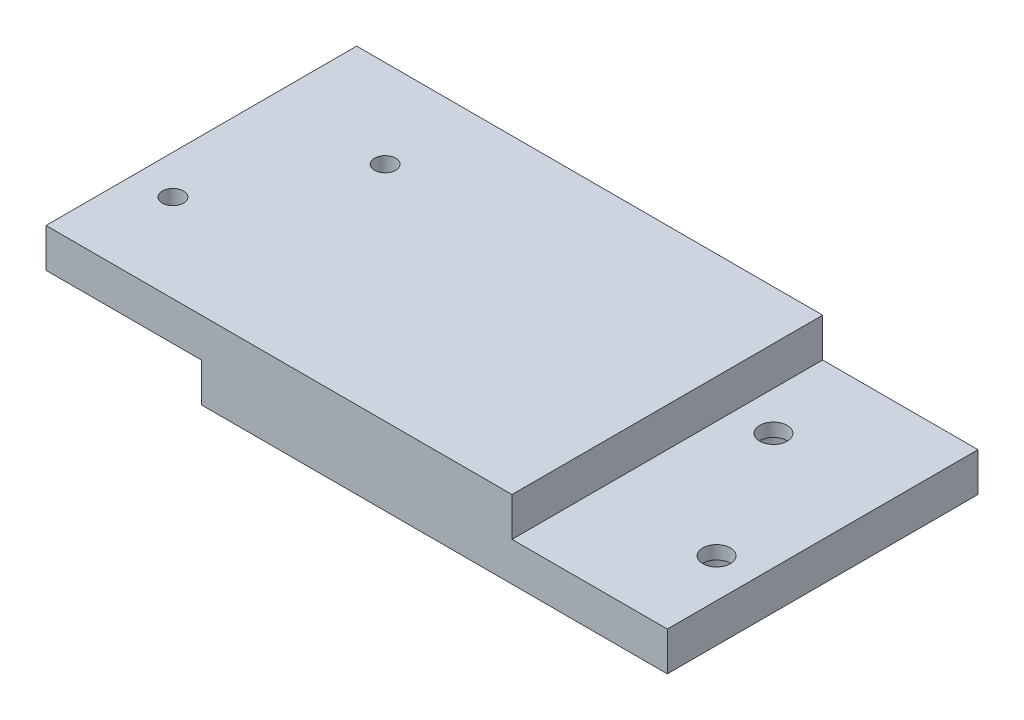
SolidWorks part; units mm, degrees
material "6061-T6 (SS)"
ref_plane "Front Plane" through (0, 0, 0) normal (0, 0, 1) x (1, 0, 0)
ref_plane "Top Plane" through (0, 0, 0) normal (0, 1, 0) x (1, 0, 0)
ref_plane "Right Plane" through (0, 0, 0) normal (1, 0, 0) x (0, 0, -1)
sketch "Sketch1" plane through (0, 0, 0) normal (0, 0, 1) x (1, 0, 0)
  line L1 (0, 0) -> (101.6, 0)
  line L2 (0, 0) -> (0, 12.7)
  line L3 (0, 12.7) -> (101.6, 12.7)
  line L4 (101.6, 0) -> (101.6, 12.7)
  line L5 (0, 0) -> (25.4, 0)
  line L6 (0, 0) -> (0, 6.35)
  line L7 (0, 6.35) -> (25.4, 6.35)
  line L8 (25.4, 0) -> (25.4, 6.35)
  line L9 (101.6, 12.7) -> (76.2, 12.7)
  line L10 (101.6, 12.7) -> (101.6, 6.35)
  line L11 (101.6, 6.35) -> (76.2, 6.35)
  line L12 (76.2, 12.7) -> (76.2, 6.35)
  dimension "D1" = 6.35
  dimension "D2" = 6.35
  dimension "D3" = 12.7
  dimension "D4" = 101.6
  dimension "D5" = 25.4
  dimension "D6" = 25.4
extrude "Boss-Extrude1" add sketch "Sketch1" along normal blind 50.8 contours L12 L3 L2 L7 L8 L1 L4 L11
sketch "Sketch2" plane through (0, 0, 0) normal (0, 1, 0) x (1, 0, 0)
  line L0 (6.35, -36.3985) -> (19.05, -14.4015) construction
  line L1 (19.05, -14.4015) -> (82.55, -14.4015) construction
  line L2 (82.55, -14.4015) -> (95.25, -36.3985) construction
  line L3 (95.25, -36.3985) -> (6.35, -36.3985) construction
  line L4 (101.6, -50.8) -> (101.6, 0) construction
  line L5 (6.35, -36.3985) -> (0, -36.3985) construction
  line L6 (0, -50.8) -> (0, 0) construction
  line L7 (95.25, -36.3985) -> (101.6, -36.3985) construction
  point P7 (101.6, -25.4)
  point P8 (88.9, -25.4)
  dimension "D1" = 120
  dimension "D2" = 120
  dimension "D3" = 63.5
  dimension "D4" = 88.9
hole_wizard "#8-32 Tapped Hole1" positions "Sketch3" profile "Sketch5" tap size "#8-32" standard "ANSI Inch" end condition through all
sketch "Sketch3" plane through (0, 12.7, 0) normal (0, 1, 0) x (1, 0, 0)
  point P0 (6.35, -36.3985)
  point P3 (19.05, -14.4015)
sketch "Sketch5" plane through (6.35, 12.7, 36.3985) normal (1, 0, 0) x (0, 0, 1)
  line L0 (0, 0) -> (0, 12.7)
  line L1 (0, 12.7) -> (1.7272, 12.7)
  line L2 (1.7272, 12.7) -> (1.7272, 0)
  line L5 (1.7272, 0) -> (0, 0)
  line L11 (0, -6.35) -> (0, 107.95) construction
  dimension "Thru Tap Drill Dia." = 3.4544
  dimension "Thru Tap Drill Depth" = 12.7
cosmetic thread "Hole Thread1" parameters "D2"=4.1656
cosmetic thread "Hole Thread2" parameters "D2"=4.1656
hole_wizard "CBORE for #8 Socket Head Cap Screw1" positions "Sketch6" profile "Sketch7" counterbore size "#8" standard "ANSI Inch" end condition through all
sketch "Sketch6" plane through (0, 0, 0) normal (0, -1, 0) x (-1, 0, 0)
  point P0 (-95.25, -36.3985)
  point P3 (-82.55, -14.4015)
sketch "Sketch7" plane through (95.25, 0, 36.3985) normal (1, 0, 0) x (0, 0, -1)
  line L0 (0, 0) -> (0, 12.7)
  line L1 (0, 12.7) -> (2.2479, 12.7)
  line L3 (2.2479, 12.7) -> (2.2479, 4.1656)
  line L4 (2.2479, 4.1656) -> (3.9688, 4.1656)
  line L5 (3.9688, 4.1656) -> (3.9688, 0)
  line L7 (3.9688, 0) -> (0, 0)
  line L11 (0, -6.35) -> (0, 107.95) construction
  dimension "Thru Hole Dia." = 4.4958
  dimension "Thru Hole Depth" = 12.7
  dimension "C'Bore Dia." = 7.9375
  dimension "C'Bore Depth" = 4.1656
